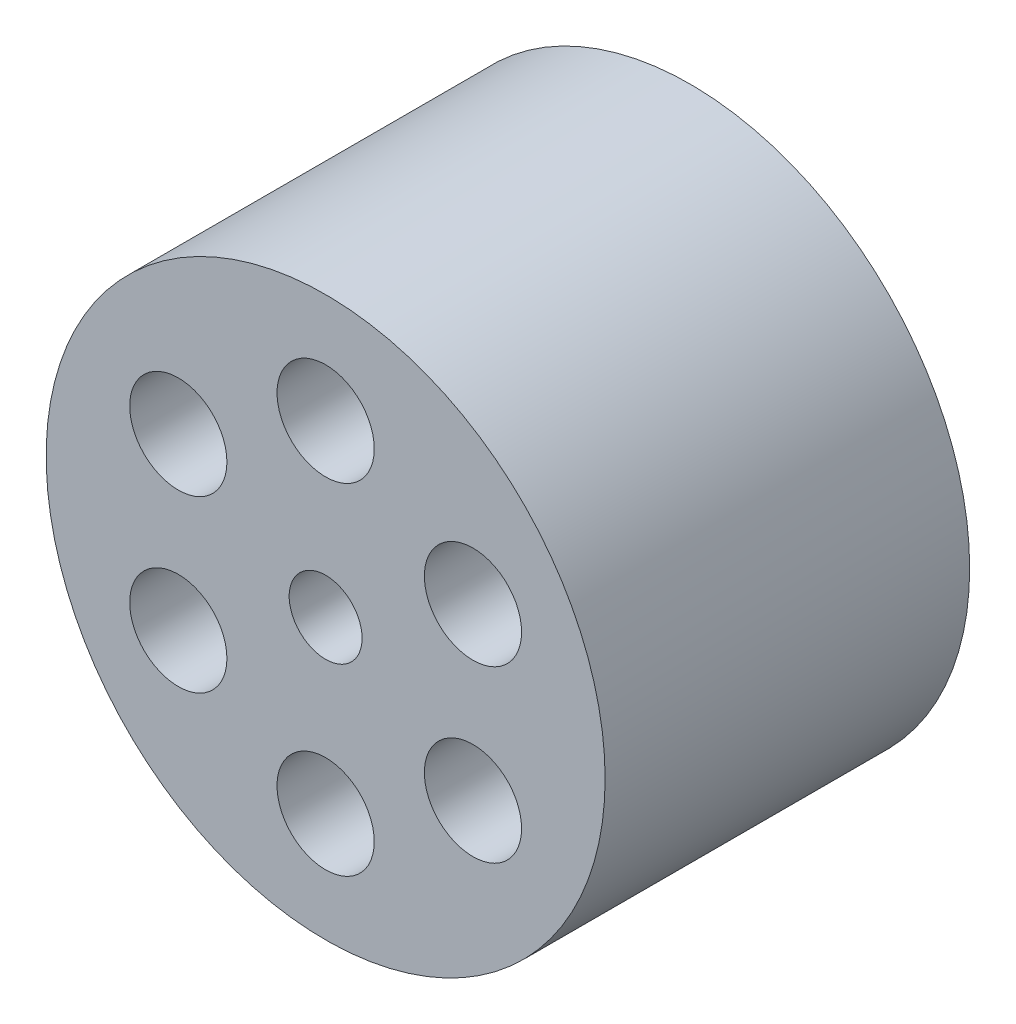
SolidWorks part; units mm, degrees
ref_plane "Front" through (0, 0, 0) normal (0, 0, 1) x (1, 0, 0)
ref_plane "Top" through (0, 0, 0) normal (0, 1, 0) x (1, 0, 0)
ref_plane "Right" through (0, 0, 0) normal (1, 0, 0) x (0, 0, -1)
sketch "Esquisse1" plane through (0, 0, 0) normal (0, 0, 1) x (1, 0, 0)
  line L0 (0, 0) -> (0, 14) construction
  circle A0 centre (0, 0) radius 23
  circle A1 centre (0, 0) radius 3
  circle A2 centre (0, 14) radius 4
  circle A3 centre (12.1244, 7) radius 4
  circle A4 centre (12.1244, -7) radius 4
  circle A5 centre (0, -14) radius 4
  circle A6 centre (-12.1244, -7) radius 4
  circle A7 centre (-12.1244, 7) radius 4
  point P18 (0, 0)
  dimension "D1" = 6
  dimension "D2" = 46
  dimension "D3" = 8
  dimension "D4" = 14
  dimension "D5" = 6
extrude "Boss.-Extru.1" add sketch "Esquisse1" along normal blind 30
